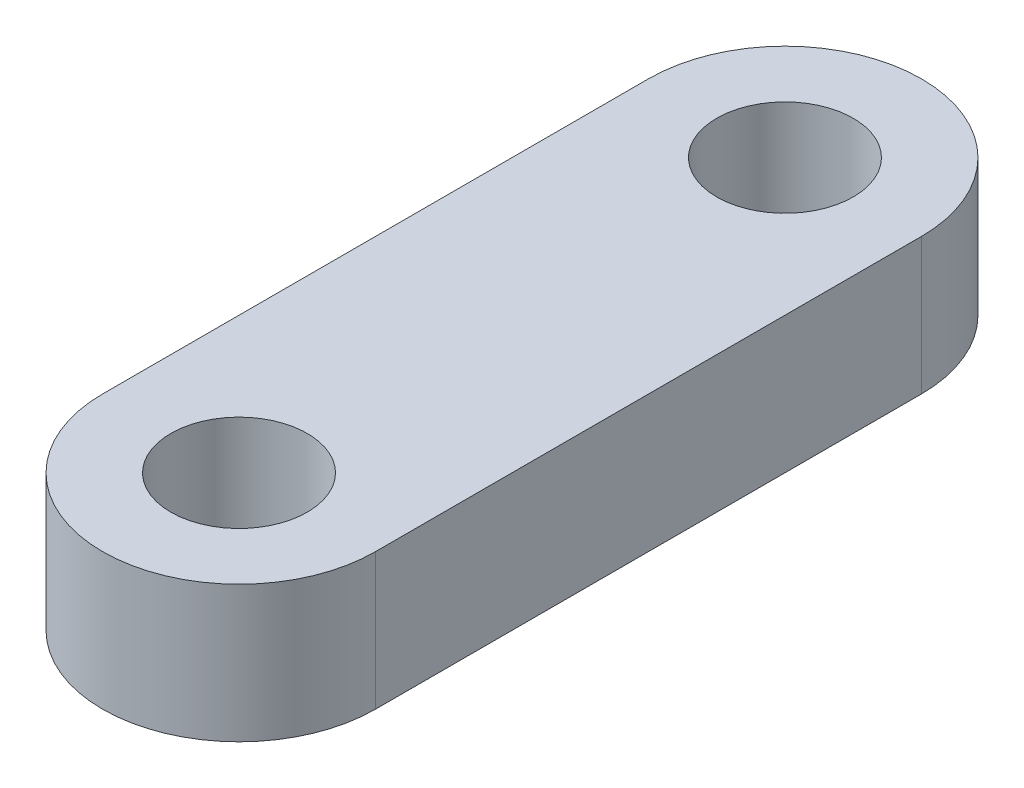
SolidWorks part; units mm, degrees
ref_plane "Front" through (0, 0, 0) normal (0, 0, 1) x (1, 0, 0)
ref_plane "Top" through (0, 0, 0) normal (0, 1, 0) x (1, 0, 0)
ref_plane "Right" through (0, 0, 0) normal (1, 0, 0) x (0, 0, -1)
sketch "Sketch1" plane through (0, 0, 0) normal (0, 1, 0) x (1, 0, 0)
  line L1 (-5, -10) -> (5, -10) construction
  line L2 (-5, -10) -> (-5, 10)
  line L3 (-5, 10) -> (5, 10) construction
  line L4 (5, -10) -> (5, 10)
  line L5 (-5, -10) -> (5, 10) construction
  line L6 (-5, 10) -> (5, -10) construction
  arc A0 (-5, 10) -> (5, 10) centre (0, 10) cw
  arc A1 (-5, -10) -> (5, -10) centre (0, -10) ccw
  point P0 (0, 0)
  dimension "D1" = 10
  dimension "D2" = 20
extrude "Boss-Extrude1" add sketch "Sketch1" along normal blind 5
sketch "Sketch2" plane through (0, 5, 0) normal (0, 1, 0) x (1, 0, 0)
  circle A0 centre (0, 10) radius 2.5
  circle A1 centre (0, -10) radius 2.5
  dimension "D1" = 5
extrude "Cut-Extrude1" cut sketch "Sketch2" against normal through all
